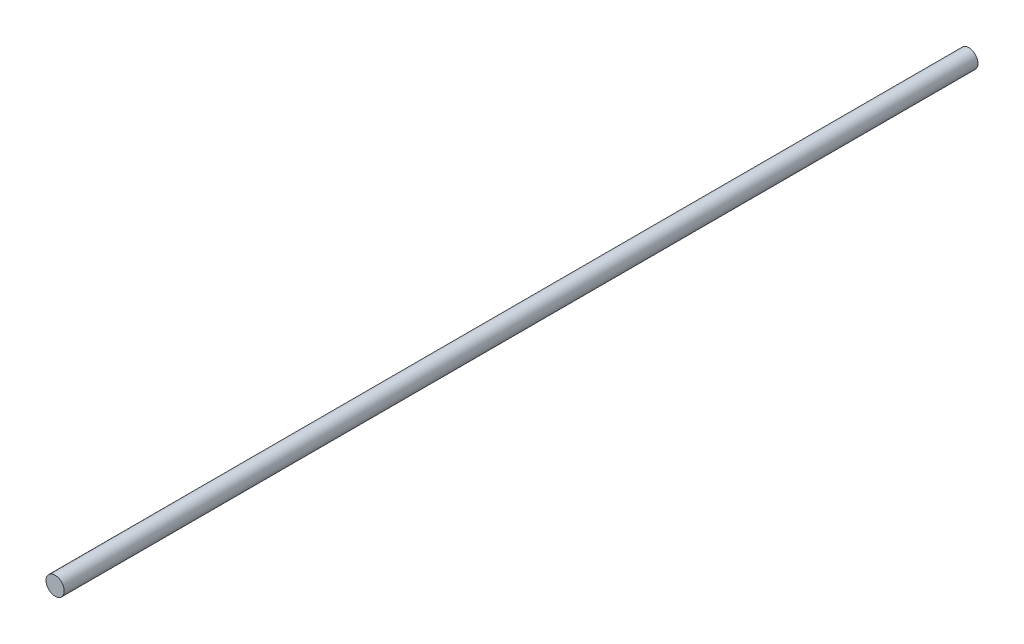
SolidWorks part; units mm, degrees
ref_plane "Plano frontal" through (0, 0, 0) normal (0, 0, 1) x (1, 0, 0)
ref_plane "Plano superior" through (0, 0, 0) normal (0, 1, 0) x (1, 0, 0)
ref_plane "Plano direito" through (0, 0, 0) normal (1, 0, 0) x (0, 0, -1)
sketch "Esboço1" plane through (0, 0, 0) normal (0, 0, 1) x (1, 0, 0)
  circle A0 centre (0, 0) radius 1.5
  dimension "D1" = 3
extrude "Ressalto-extrusão1" add sketch "Esboço1" along normal blind 150
